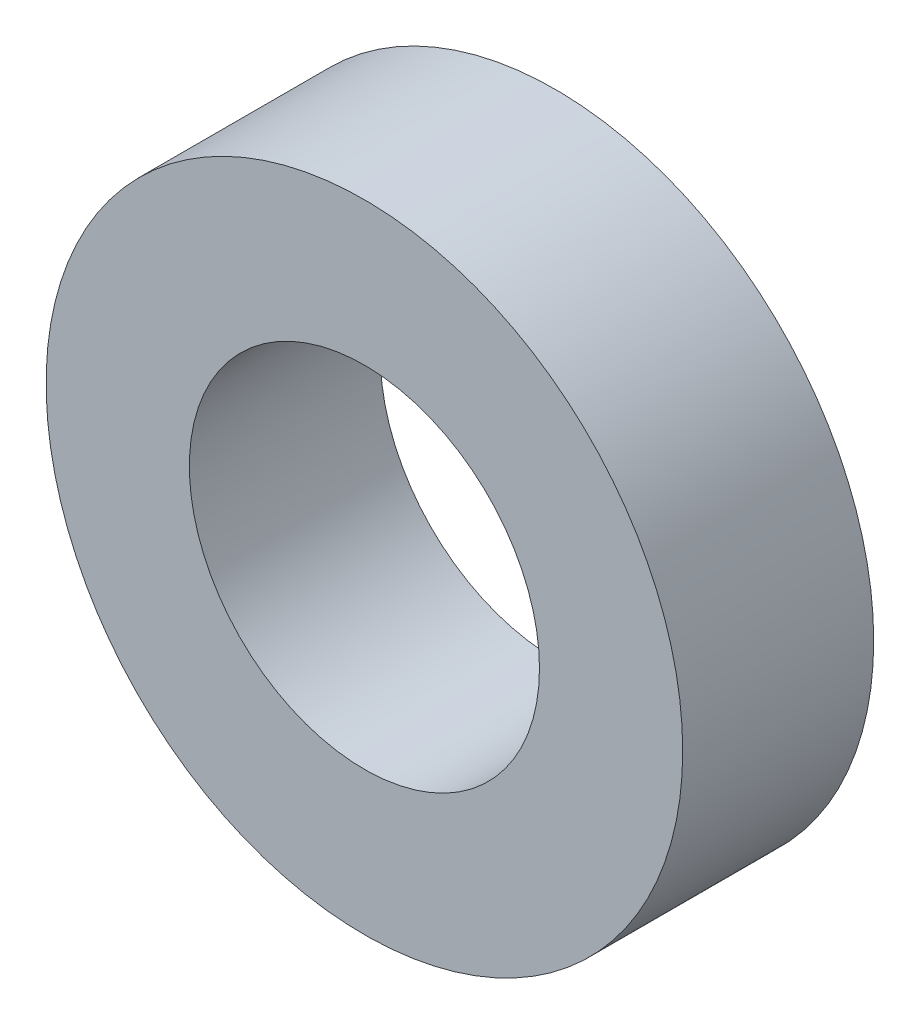
SolidWorks part; units mm, degrees
ref_plane "Front Plane" through (0, 0, 0) normal (0, 0, 1) x (1, 0, 0)
ref_plane "Top Plane" through (0, 0, 0) normal (0, 1, 0) x (1, 0, 0)
ref_plane "Right Plane" through (0, 0, 0) normal (1, 0, 0) x (0, 0, -1)
sketch "Sketch1" plane through (0, 0, 0) normal (0, 0, 1) x (1, 0, 0)
  circle A0 centre (0, 0) radius 2.75
  circle A1 centre (0, 0) radius 5
  dimension "D1" = 5.5
  dimension "D2" = 10
extrude "Boss-Extrude1" add sketch "Sketch1" along normal blind 3
